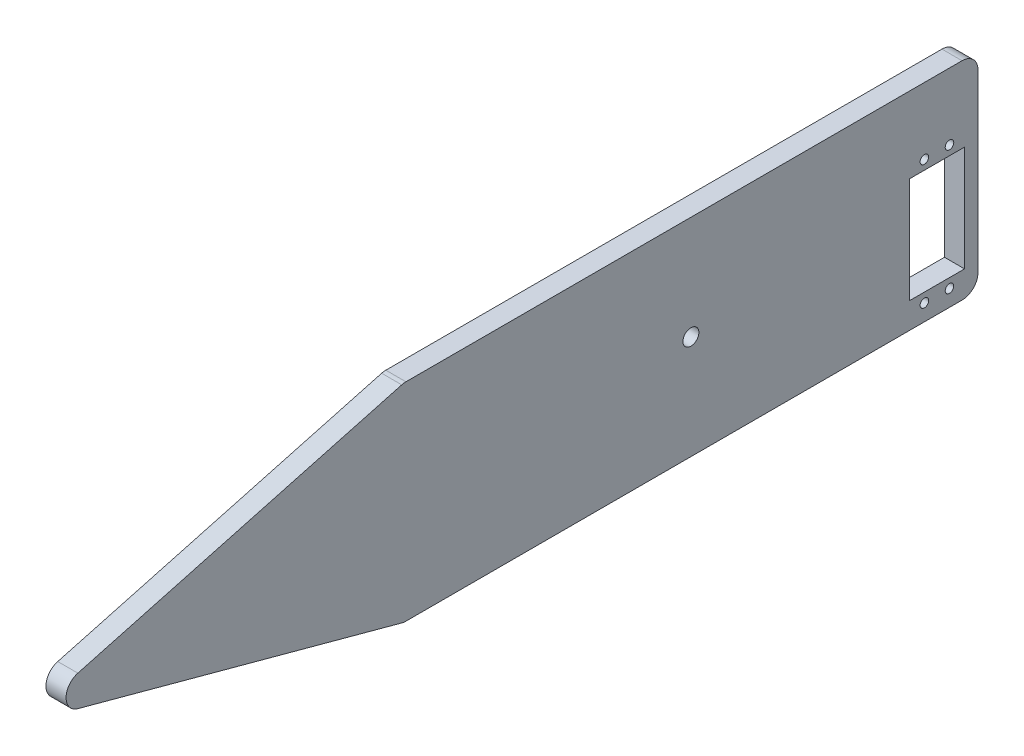
SolidWorks part; units mm, degrees
ref_plane "Front Plane" through (0, 0, 0) normal (1, 0, 0) x (0, 1, 0)
ref_plane "Top Plane" through (0, 0, 0) normal (0, 0, 1) x (0, 1, 0)
ref_plane "Right Plane" through (0, 0, 0) normal (0, 1, 0) x (-1, 0, 0)
sketch "Sketch1" plane through (0, 0, 0) normal (1, 0, 0) x (0, 1, 0)
  line L0 (-41.275, 114.3) -> (-41.275, -114.3)
  line L1 (-41.275, -114.3) -> (41.275, -114.3)
  line L2 (41.275, -114.3) -> (41.275, 114.3)
  line L3 (41.275, 114.3) -> (0, 266.7)
  line L4 (0, 266.7) -> (-41.275, 114.3)
  line L5 (0, 266.7) -> (0, 0) construction
  line L6 (-41.275, 114.3) -> (0, 114.3) construction
  line L7 (0, 114.3) -> (41.275, 114.3) construction
  circle A0 centre (0, 0) radius 6.35 construction
  circle A1 centre (0, 0) radius 14.351 construction
  circle A2 centre (0, 0) radius 3.175
  dimension "D5" = 12.7
  dimension "D6" = 28.702
  dimension "D7" = 6.35
  dimension "D1" = 228.6
  dimension "D2" = 381
  dimension "D3" = 114.3
  dimension "D4" = 82.55
sketch "Sketch2" plane through (0, 0, 0) normal (1, 0, 0) x (0, 1, 0)
  line L0 (-37.25, -97.95) -> (-30, -97.95) construction
  line L1 (-30, -87.95) -> (10, -87.95)
  line L2 (-30, -87.95) -> (-30, -107.95)
  line L3 (-30, -107.95) -> (10, -107.95)
  line L9 (-30, -88.95) -> (-37.25, -88.95)
  line L10 (-30, -88.95) -> (-30, -106.95)
  line L11 (-30, -106.95) -> (-37.25, -106.95)
  line L12 (-37.25, -88.95) -> (-37.25, -106.95)
  line L13 (10, -87.95) -> (10, -107.95)
  line L14 (-10, -87.95) -> (-10, -107.95) construction
  line L15 (10, -106.95) -> (17.25, -106.95)
  line L16 (17.25, -88.95) -> (17.25, -106.95)
  line L17 (10, -88.95) -> (17.25, -88.95)
  line L18 (-34.75, -88.95) -> (-34.75, -92.95) construction
  line L19 (-34.75, -92.95) -> (-34.75, -102.95) construction
  line L20 (-34.75, -102.95) -> (-34.75, -106.95) construction
  line L21 (14.75, -102.95) -> (14.75, -106.95) construction
  line L22 (14.75, -92.95) -> (14.75, -102.95) construction
  line L23 (14.75, -88.95) -> (14.75, -92.95) construction
  line L24 (0, -97.95) -> (10, -97.95) construction
  line L25 (0, 0) -> (0, -97.95) construction
  line L26 (-41.275, -114.3) -> (41.275, -114.3) construction
  circle A0 centre (0, -97.95) radius 3.9853
  circle A1 centre (-34.75, -92.95) radius 2.1
  dimension "D9" = 4.2
  dimension "D1" = 40
  dimension "D2" = 54.5
  dimension "D3" = 10
  dimension "D4" = 49.5
  dimension "D5" = 20
  dimension "D6" = 1
  dimension "D7" = 10
  dimension "D8" = 6.35
extrude "Boss-Extrude2" add sketch "Sketch1" along normal mid plane 8.001
fillet "Fillet1" radius 6.35 5 edges at (0, 41.275, -114.3) (0, -41.275, -114.3) (0, 0, 266.7) (0, -41.275, 114.3) (0, 41.275, 114.3)
sketch "Sketch6" plane through (4.0005, 0, 0) normal (1, 0, 0) x (0, 1, 0)
  circle A0 centre (-34.75, -92.95) radius 1.7
  circle A1 centre (-34.75, -102.95) radius 1.7
  circle A2 centre (14.75, -92.95) radius 1.7
  circle A3 centre (14.75, -102.95) radius 1.7
  dimension "D1" = 3.4
extrude "Cut-Extrude2" cut sketch "Sketch6" against normal through all
sketch "Sketch5" plane through (4.0005, 0, 0) normal (1, 0, 0) x (0, 1, 0)
  line L8 (11, -108.95) -> (11, -86.95)
  line L9 (-31, -108.95) -> (11, -108.95)
  line L10 (-31, -86.95) -> (-31, -108.95)
  line L11 (11, -86.95) -> (-31, -86.95)
  line L12 (11, -108.95) -> (11, -86.95)
  line L13 (-31, -108.95) -> (11, -108.95)
  line L14 (-31, -86.95) -> (-31, -108.95)
  line L15 (11, -86.95) -> (-31, -86.95)
  dimension "D1" = 1
extrude "Cut-Extrude1" cut sketch "Sketch5" against normal through all
